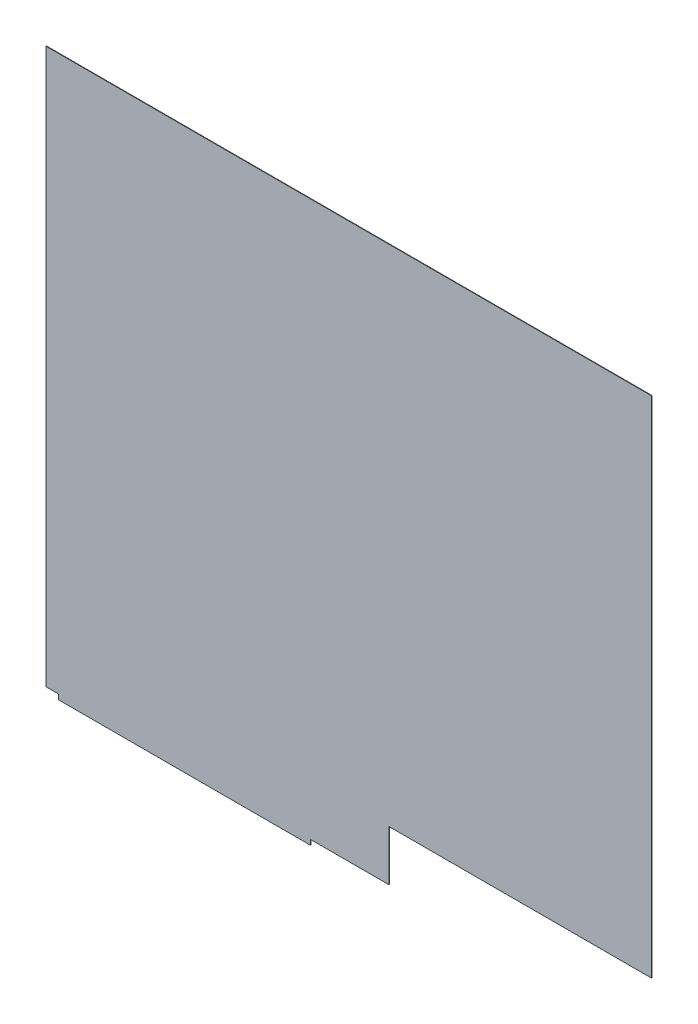
SolidWorks part; units mm, degrees
ref_plane "Front Plane" through (0, 0, 0) normal (0, 0, 1) x (1, 0, 0)
ref_plane "Top Plane" through (0, 0, 0) normal (0, 1, 0) x (1, 0, 0)
ref_plane "Right Plane" through (0, 0, 0) normal (1, 0, 0) x (0, 0, -1)
sketch "Sketch1" plane through (0, 0, 0) normal (0, 0, 1) x (1, 0, 0)
  line L0 (-2830, -2800) -> (-2950, -2800)
  line L1 (450, -2800) -> (-330, -2800)
  line L2 (3050, -2300) -> (3050, 2700)
  line L3 (3050, 2700) -> (-2950, 2700)
  line L4 (-2950, -2800) -> (-2950, 2700)
  line L5 (2599.6877, -2386.5985) -> (-2950, 2700) construction
  line L6 (3050, 2700) -> (-2950, -2800) construction
  line L7 (3050, -2300) -> (450, -2300)
  line L10 (450, -2300) -> (450, -2800)
  line L11 (3050, -2300) -> (450, -2800) construction
  line L12 (1682.2233, -2563.034) -> (450, -2300) construction
  line L14 (-2830, -2800) -> (-2830, -2850)
  line L15 (-2830, -2850) -> (-330, -2850)
  line L16 (-330, -2800) -> (-330, -2850)
  line L17 (-2830, -2800) -> (-330, -2850) construction
  line L18 (-2830, -2850) -> (-330, -2800) construction
  point P0 (50.1814, -49.8337)
  point P9 (1682.2233, -2563.034)
  point P15 (-1580, -2825)
  dimension "D1" = 5500
  dimension "D2" = 6000
  dimension "D3" = 500
  dimension "D4" = 2600
  dimension "D5" = 780
  dimension "D6" = 2500
  dimension "D7" = 50
extrude "Boss-Extrude1" add sketch "Sketch1" along normal blind 5
